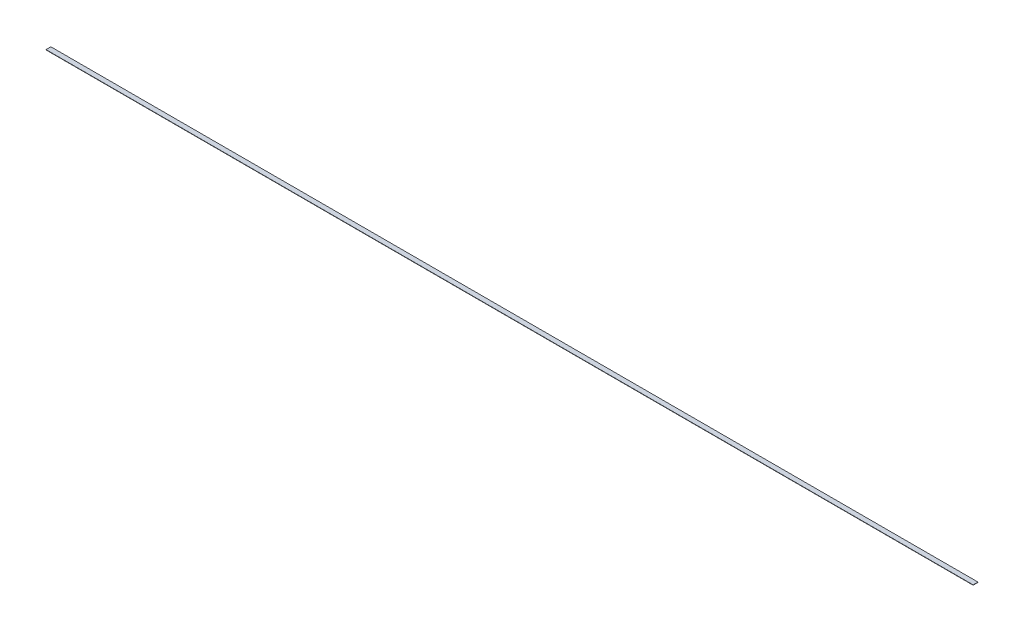
SolidWorks part; units mm, degrees
ref_plane "Front Plane" through (0, 0, 0) normal (0, 0, 1) x (1, 0, 0)
ref_plane "Top Plane" through (0, 0, 0) normal (0, 1, 0) x (1, 0, 0)
ref_plane "Right Plane" through (0, 0, 0) normal (1, 0, 0) x (0, 0, -1)
sketch "Sketch1" plane through (0, 0, 0) normal (0, 1, 0) x (1, 0, 0)
  line L1 (0, 0) -> (9702.8, 0)
  line L2 (0, 0) -> (0, 50.8)
  line L3 (0, 50.8) -> (9702.8, 50.8)
  line L4 (9702.8, 0) -> (9702.8, 50.8)
  dimension "D1" = 50.8
  dimension "D2" = 9702.8
extrude "Boss-Extrude1" add sketch "Sketch1" along normal blind 3.175
